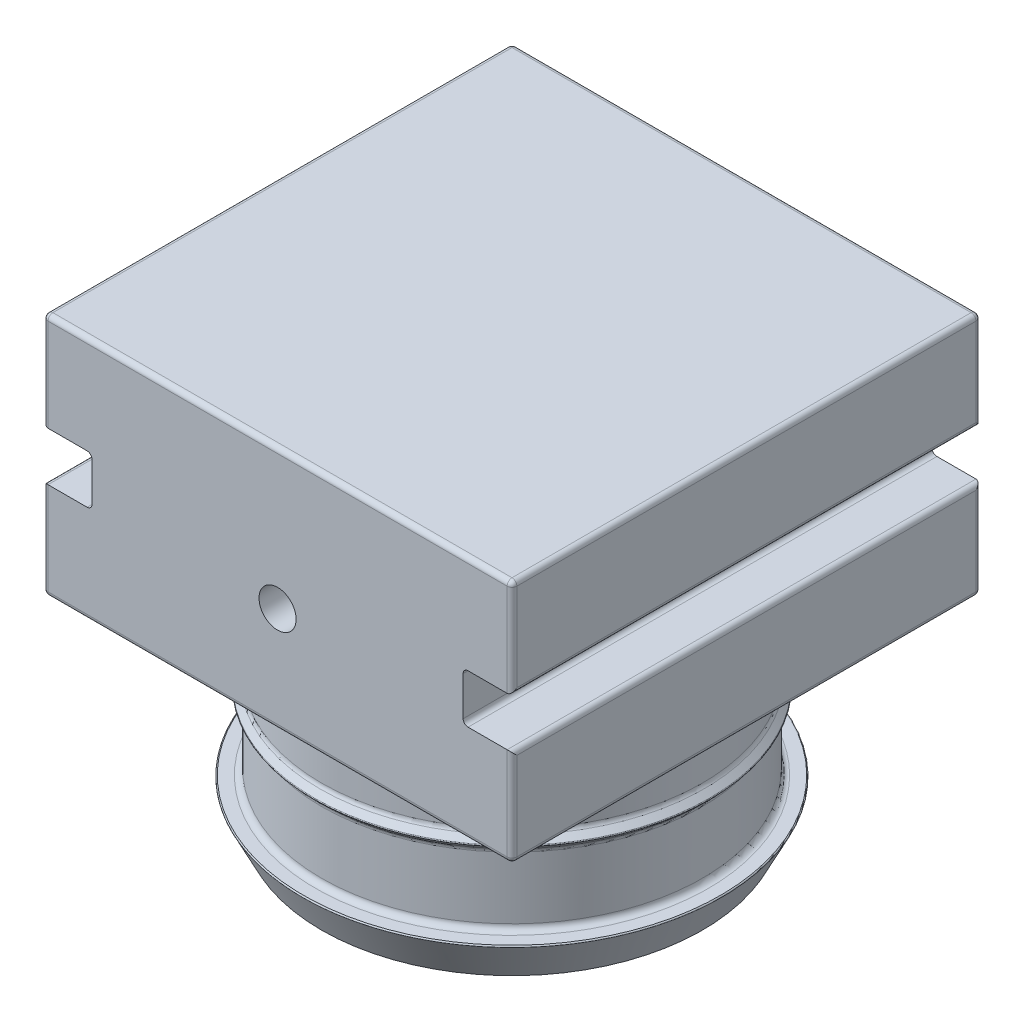
SolidWorks part; units mm, degrees
ref_plane "Front Plane" through (0, 0, 0) normal (0, 0, 1) x (1, 0, 0)
ref_plane "Top Plane" through (0, 0, 0) normal (0, 1, 0) x (1, 0, 0)
ref_plane "Right Plane" through (0, 0, 0) normal (1, 0, 0) x (0, 0, -1)
sketch "Sketch1" plane through (0, 0, 0) normal (0, 0, 1) x (1, 0, 0)
  line L0 (0, 1017.6623) -> (0, 12.7) construction
  line L1 (0, -12.7) -> (19.5, -12.7)
  line L8 (0, 7.3) -> (0, -12.7)
  line L9 (19.5, -12.7) -> (21.5, -8.7)
  line L25 (7.9375, 6.35) -> (0, 6.35) construction
  line L32 (21.5, -8.7) -> (19.5, -8.7)
  line L33 (19.5, -8.7) -> (19.5, -1.4938)
  line L34 (19.5, 0.0938) -> (20.2938, -0.7)
  line L35 (20.2938, -0.7) -> (19.5, -1.4938)
  line L36 (20.2938, -0.7) -> (9.4, -0.7) construction
  line L40 (0, 7.3) -> (0, -7.7377) construction
  line L41 (0, 7.3) -> (19.5, 7.3)
  line L42 (19.5, 7.3) -> (19.5, 0.0938)
  dimension "D7" = 2
  dimension "D4" = 16
  dimension "D2" = 4
  dimension "D3" = 19.5
  dimension "D5" = 0.7937
  dimension "D10" = 12
  dimension "D11" = 45
  dimension "D9" = 0.7937
revolve "Revolve1" add sketch "Sketch1" angle 360 about L0
sketch "Sketch2" plane through (0, 7.3, 0) normal (0, 1, 0) x (1, 0, 0)
  line L1 (24, -24) -> (-24, -24)
  line L2 (24, -24) -> (24, 24)
  line L3 (24, 24) -> (-24, 24)
  line L4 (-24, -24) -> (-24, 24)
  line L5 (24, -24) -> (-24, 24) construction
  line L6 (24, 24) -> (-24, -24) construction
  point P0 (0, 0)
  dimension "D1" = 48
  dimension "D2" = 48
extrude "Boss-Extrude1" add sketch "Sketch2" along normal blind 25
sketch "Sketch3" plane through (0, 0, 24) normal (0, 0, 1) x (1, 0, 0)
  line L0 (24, 19.8) -> (-24, 19.8) construction
  line L1 (24, 32.3) -> (24, 7.3) construction
  line L2 (-24, 32.3) -> (-24, 7.3) construction
  line L3 (0, 7.3) -> (0, 32.3) construction
  line L4 (24, 17.3) -> (19, 17.3)
  line L5 (24, 17.3) -> (24, 22.3)
  line L8 (24, 22.3) -> (19, 22.3)
  line L9 (19, 17.3) -> (19, 22.3)
  line L10 (-24, 32.3) -> (24, 32.3) construction
  line L11 (-24, 17.3) -> (-24, 22.3)
  line L26 (-24, 22.3) -> (-19, 22.3)
  line L27 (-19, 17.3) -> (-19, 22.3)
  line L28 (-24, 17.3) -> (-19, 17.3)
  point P10 (19, 19.8)
  dimension "D2" = 2.5
  dimension "D3" = 5
  dimension "D1" = 2.5
extrude "Cut-Extrude2" cut sketch "Sketch3" against normal through all
sketch "Sketch4" plane through (0, -12.7, 0) normal (0, -1, 0) x (1, 0, 0)
  circle A0 centre (0, 0) radius 2.41
  dimension "D1" = 4.82
extrude "Cut-Extrude3" cut sketch "Sketch4" against normal blind 33
sketch "Sketch5" plane through (0, 0, 24) normal (0, 0, 1) x (1, 0, 0)
  line L3 (0, -12.6439) -> (0, 27.2439) construction
  line L5 (0, 201017.6623) -> (0, 12.7) construction
  point P0 (0, 18.05)
  point P3 (-9.75, 18.05)
  point P9 (0, 7.3)
hole_wizard "#10-24 Tapped Hole1" positions "Sketch6" profile "Sketch7" tap size "#10-24" standard "ANSI Inch"
sketch "Sketch6" plane through (0, 0, 24) normal (0, 0, 1) x (1, 0, 0)
  point P0 (0, 18.05)
sketch "Sketch7" plane through (0, 18.05, 24) normal (1, 0, 0) x (0, -1, 0)
  line L0 (0, 0) -> (0, 24.1408)
  line L1 (0, 24.1408) -> (1.8986, 23)
  line L2 (1.8986, 23) -> (1.8986, 0)
  line L5 (1.8986, 0) -> (0, 0)
  line L10 (0, 24.1408) -> (-1.8987, 23) construction
  line L11 (0, -6.35) -> (0, 107.95) construction
  dimension "Tap Drill Dia." = 3.7973
  dimension "Tap Drill Depth" = 23
  dimension "Drill Angle" = 118
cosmetic thread "Hole Thread1" parameters "D1"=6.35, "D2"=4.826
fillet "Fillet1" radius 0.1 2 edges at (0, -0.7, 20.2938) (0, -8.7, 21.5)
fillet "Fillet2" radius 0.6 4 edges at (0, 7.3, 19.5) (0, 0.0938, 19.5) (0, -1.4938, 19.5) (0, -8.7, 19.5)
fillet "Fillet3" radius 0.5 24 edges at (-24, 22.3, 0) (-24, 17.3, 0) (-24, 27.3, -24) (-24, 12.3, -24) (-24, 12.3, 24) (-24, 27.3, 24) (-19, 22.3, 0) (-19, 17.3, 0) (19, 17.3, 0) (19, 22.3, 0) (24, 17.3, 0) (24, 22.3, 0) (24, 12.3, -24) (24, 27.3, -24) (24, 12.3, 24) (24, 27.3, 24) (0, 32.3, 24) (24, 32.3, 0) (-24, 32.3, 0) (0, 32.3, -24) (0, 7.3, -24) (-24, 7.3, 0) (0, 7.3, 24) (24, 7.3, 0)
